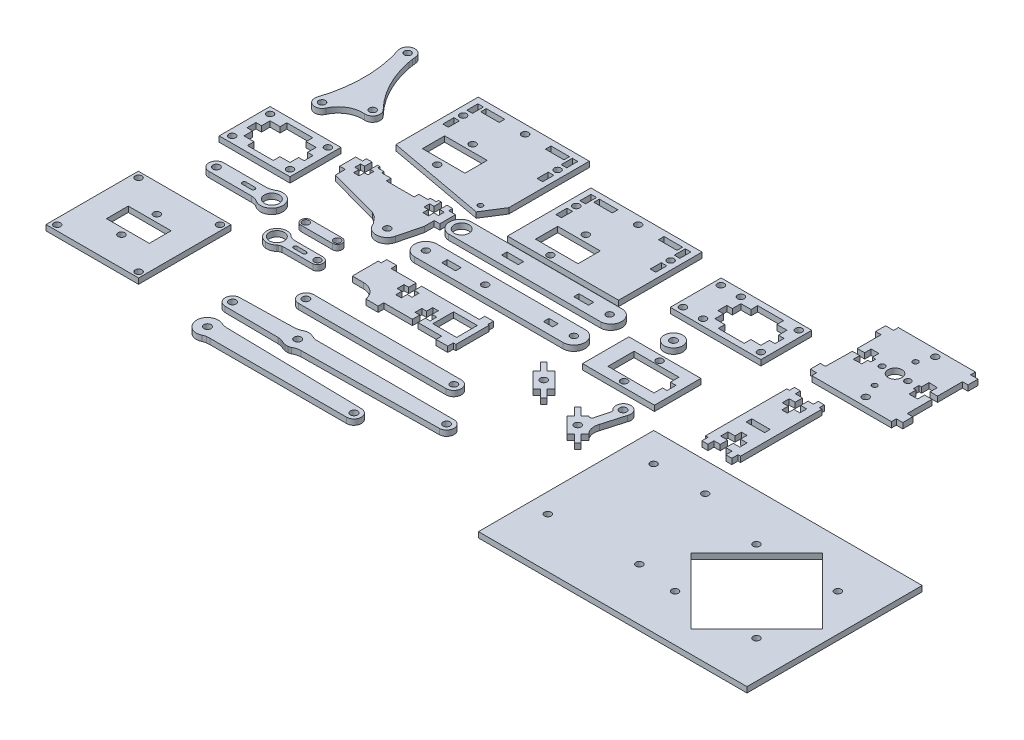
SolidWorks part; units mm, degrees
ref_plane "Front Plane" through (0, 0, 0) normal (0, 0, 1) x (1, 0, 0)
ref_plane "Top Plane" through (0, 0, 0) normal (0, 1, 0) x (1, 0, 0)
ref_plane "Right Plane" through (0, 0, 0) normal (1, 0, 0) x (0, 0, -1)
sketch "Sketch6" plane through (0, 0, -6.8736) normal (0, 1, 0) x (1, 0, 0)
  line L36 (172.3993, 17.524) -> (172.3993, 14.7799)
  line L37 (172.3993, 14.7799) -> (176.2794, 14.7799)
  line L38 (176.2794, 14.7799) -> (176.2794, 10.7799)
  line L39 (176.2794, 10.7799) -> (173.032, 10.7799)
  line L40 (173.032, 10.7799) -> (173.032, 7.063)
  line L41 (173.032, 7.063) -> (176.2794, 7.063)
  line L42 (176.2794, 7.063) -> (176.2794, 3.563)
  line L43 (176.2794, 3.563) -> (179.2794, 3.563)
  line L44 (179.2794, 3.563) -> (179.2794, 7.063)
  line L45 (179.2794, 7.063) -> (182.5439, 7.063)
  line L46 (182.5439, 7.063) -> (182.5439, 10.7799)
  line L47 (182.5439, 10.7799) -> (179.2794, 10.7799)
  line L48 (179.2794, 10.7799) -> (179.2794, 14.7799)
  line L49 (179.2794, 14.7799) -> (182.1277, 14.7799)
  line L50 (182.1277, 14.7799) -> (182.1277, 17.4216)
  line L54 (182.1277, -32.5784) -> (182.1277, -29.2201)
  line L55 (182.1277, -29.2201) -> (178.7635, -29.2201)
  line L56 (178.7635, -29.2201) -> (178.7635, -25.2201)
  line L57 (178.7635, -25.2201) -> (182.3404, -25.2201)
  line L58 (182.3404, -25.2201) -> (182.3404, -21.2526)
  line L59 (182.3404, -21.2526) -> (178.7635, -21.2526)
  line L60 (178.7635, -21.2526) -> (178.7635, -17.7526)
  line L61 (178.7635, -17.7526) -> (175.7635, -17.7526)
  line L62 (175.7635, -17.7526) -> (175.7635, -21.2526)
  line L63 (175.7635, -21.2526) -> (171.9828, -21.2526)
  line L64 (171.9828, -21.2526) -> (171.9828, -25.2201)
  line L65 (171.9828, -25.2201) -> (175.7635, -25.2201)
  line L66 (175.7635, -25.2201) -> (175.7635, -29.2201)
  line L67 (175.7635, -29.2201) -> (172.3993, -29.2201)
  line L68 (172.3993, -29.2201) -> (172.3993, -32.476)
  line L72 (172.2635, -8.7201) -> (182.2635, -8.7201)
  line L73 (182.2635, -8.7201) -> (182.2635, -11.7201)
  line L74 (182.2635, -11.7201) -> (172.2635, -11.7201)
  line L75 (172.2635, -11.7201) -> (172.2635, -8.7201)
  line L132 (186.7635, -29.2201) -> (185.3957, -29.2201)
  line L133 (185.3957, -29.2201) -> (185.3957, -32.5784)
  line L134 (167.7635, -29.2201) -> (169.1313, -29.2201)
  line L135 (169.1313, -29.2201) -> (169.1313, -32.476)
  line L136 (169.1313, 17.524) -> (169.1313, 14.7799)
  line L137 (169.1313, 14.7799) -> (167.7635, 14.7799)
  line L138 (185.3957, 17.4216) -> (185.3957, 14.7799)
  line L139 (185.3957, 14.7799) -> (186.7635, 14.7799)
  line L140 (167.7635, 14.7799) -> (167.7635, -29.2201)
  line L141 (169.1313, -32.476) -> (172.3993, -32.476)
  line L142 (182.1277, 17.4216) -> (185.3957, 17.4216)
  line L143 (186.7635, 14.7799) -> (186.7635, -29.2201)
  line L144 (185.3957, -32.5784) -> (182.1277, -32.5784)
  line L145 (169.1313, 17.524) -> (172.3993, 17.524)
  dimension "D6" = 1.3678
  dimension "D7" = 3.268
extrude "Boss-Extrude1" add sketch "Sketch6" along normal blind 3
sketch "Sketch12" plane through (0, 0, 0) normal (0, 1, 0) x (1, 0, 0)
  line L100 (4.3413, 14.5567) -> (85.6849, 14.5567)
  line L101 (3.678, 2.7449) -> (86.3482, 2.7449)
  line L103 (67.0131, 9.9945) -> (75.0131, 9.9945)
  line L104 (67.0131, 9.9945) -> (67.0131, 7.1945)
  line L105 (67.0131, 7.1945) -> (75.0131, 7.1945)
  line L106 (75.0131, 9.9945) -> (75.0131, 7.1945)
  line L107 (28.0131, 10.0945) -> (37.0131, 10.0945)
  line L108 (28.0131, 10.0945) -> (28.0131, 7.1945)
  line L109 (28.0131, 7.1945) -> (37.0131, 7.1945)
  line L110 (37.0131, 10.0945) -> (37.0131, 7.1945)
  arc A87 (4.3413, 14.5567) -> (3.678, 2.7449) centre (4.3413, 8.6322) ccw
  arc A88 (85.6849, 14.5567) -> (86.3482, 2.7449) centre (85.6849, 8.6322) cw
  circle A100 centre (5.0131, 8.5945) radius 4
  circle A101 centre (85.0131, 8.5945) radius 1.82
  dimension "D29" = 3.64
  dimension "D27" = 8
extrude "Boss-Extrude3" add sketch "Sketch12" along normal blind 3 separate body
sketch "Sketch14" plane through (0, 0, 0) normal (0, 1, 0) x (1, 0, 0)
  line L0 (20.7129, 62.7973) -> (80.7867, 62.7973)
  line L1 (80.7867, 62.7973) -> (80.7867, 17.6847)
  line L2 (80.7867, 17.6847) -> (20.7129, 17.6847)
  line L3 (20.7129, 17.6847) -> (20.7129, 62.7973)
  line L4 (28.2425, 59.822) -> (38.2425, 59.822)
  line L5 (28.2425, 59.822) -> (28.2425, 56.822)
  line L6 (28.2425, 56.822) -> (38.2425, 56.822)
  line L7 (38.2425, 59.822) -> (38.2425, 56.822)
  line L8 (63.2425, 59.822) -> (73.2425, 59.822)
  line L9 (63.2425, 59.822) -> (63.2425, 56.822)
  line L10 (63.2425, 56.822) -> (73.2425, 56.822)
  line L11 (73.2425, 59.822) -> (73.2425, 56.822)
  line L12 (74.7425, 59.822) -> (77.7425, 59.822)
  line L13 (74.7425, 59.822) -> (74.7425, 53.822)
  line L14 (74.7425, 53.822) -> (77.7425, 53.822)
  line L15 (77.7425, 59.822) -> (77.7425, 53.822)
  line L16 (74.7425, 46.822) -> (77.7425, 46.822)
  line L17 (74.7425, 46.822) -> (74.7425, 40.822)
  line L18 (74.7425, 40.822) -> (77.7425, 40.822)
  line L19 (77.7425, 46.822) -> (77.7425, 40.822)
  line L20 (29.7425, 35.822) -> (52.7425, 35.822)
  line L21 (29.7425, 35.822) -> (29.7425, 23.822)
  line L22 (29.7425, 23.822) -> (52.7425, 23.822)
  line L23 (52.7425, 35.822) -> (52.7425, 23.822)
  line L24 (23.7425, 46.822) -> (26.7425, 46.822)
  line L25 (23.7425, 46.822) -> (23.7425, 40.822)
  line L26 (23.7425, 40.822) -> (26.7425, 40.822)
  line L27 (26.7425, 46.822) -> (26.7425, 40.822)
  line L28 (23.7425, 59.822) -> (26.7425, 59.822)
  line L29 (23.7425, 59.822) -> (23.7425, 53.822)
  line L30 (23.7425, 53.822) -> (26.7425, 53.822)
  line L31 (26.7425, 59.822) -> (26.7425, 53.822)
  circle A0 centre (50.7425, 58.322) radius 1.82
  circle A1 centre (41.2425, 39.4969) radius 1.82
  circle A2 centre (41.2425, 20.3569) radius 1.82
  circle A3 centre (76.2425, 50.322) radius 1.82
  circle A4 centre (25.2425, 50.322) radius 1.82
  dimension "D1" = 19.14
  dimension "D2" = 3.64
  dimension "D3" = 3.64
  dimension "D4" = 3.64
  dimension "D5" = 3.64
extrude "Boss-Extrude4" add sketch "Sketch14" along normal blind 3 separate body
sketch "Sketch18" plane through (0, 0, 0) normal (0, 1, 0) x (1, 0, 0)
  line L0 (-52.2788, 74.8705) -> (7.7767, 74.8705)
  line L1 (7.7767, 74.8705) -> (7.7767, 31.3788)
  line L2 (7.7767, 31.3788) -> (0.9291, 20.5522)
  line L3 (0.9291, 20.5522) -> (-52.2788, 30.361)
  line L4 (-52.2788, 30.361) -> (-52.2788, 74.8705)
  line L5 (-44.7078, 71.6303) -> (-34.7078, 71.6303)
  line L6 (-44.7078, 71.6303) -> (-44.7078, 68.6303)
  line L7 (-44.7078, 68.6303) -> (-34.7078, 68.6303)
  line L8 (-34.7078, 71.6303) -> (-34.7078, 68.6303)
  line L9 (-49.2078, 71.6303) -> (-46.2078, 71.6303)
  line L10 (-49.2078, 71.6303) -> (-49.2078, 65.6303)
  line L11 (-49.2078, 65.6303) -> (-46.2078, 65.6303)
  line L12 (-46.2078, 71.6303) -> (-46.2078, 65.6303)
  line L13 (-49.2078, 58.6303) -> (-46.2078, 58.6303)
  line L14 (-49.2078, 58.6303) -> (-49.2078, 52.6303)
  line L15 (-49.2078, 52.6303) -> (-46.2078, 52.6303)
  line L16 (-46.2078, 58.6303) -> (-46.2078, 52.6303)
  line L17 (-43.2078, 47.6303) -> (-20.2078, 47.6303)
  line L18 (-43.2078, 47.6303) -> (-43.2078, 35.6303)
  line L19 (-43.2078, 35.6303) -> (-20.2078, 35.6303)
  line L20 (-20.2078, 47.6303) -> (-20.2078, 35.6303)
  line L21 (-9.7078, 71.6303) -> (0.2922, 71.6303)
  line L22 (-9.7078, 71.6303) -> (-9.7078, 68.6303)
  line L23 (-9.7078, 68.6303) -> (0.2922, 68.6303)
  line L24 (0.2922, 71.6303) -> (0.2922, 68.6303)
  line L25 (1.7922, 71.6303) -> (4.7922, 71.6303)
  line L26 (1.7922, 71.6303) -> (1.7922, 65.6303)
  line L27 (1.7922, 65.6303) -> (4.7922, 65.6303)
  line L28 (4.7922, 71.6303) -> (4.7922, 65.6303)
  line L29 (1.7922, 58.6303) -> (4.7922, 58.6303)
  line L30 (1.7922, 58.6303) -> (1.7922, 52.6303)
  line L31 (1.7922, 52.6303) -> (4.7922, 52.6303)
  line L32 (4.7922, 58.6303) -> (4.7922, 52.6303)
  circle A0 centre (3.3054, 62.1514) radius 1.82
  circle A1 centre (-0.9558, 24.7244) radius 1.2998
  circle A2 centre (-31.7081, 32.1289) radius 1.82
  circle A3 centre (-31.6898, 51.2689) radius 1.82
  circle A4 centre (-47.7078, 62.1303) radius 1.82
  circle A5 centre (-22.2078, 70.1303) radius 1.82
  dimension "D1" = 3.64
  dimension "D2" = 19.14
sketch "Sketch20" plane through (0, 0, 0) normal (0, 1, 0) x (1, 0, 0)
  line L0 (-3.3445, 5.1376) -> (-6.3445, 5.1376)
  line L1 (-6.3445, -0.1855) -> (-9.5309, -12.7114)
  line L2 (-21.2346, -12.8672) -> (-24.3389, -9.2481)
  line L3 (-24.3389, -9.2481) -> (-27.0786, -7.6072)
  line L4 (-27.0786, -7.6072) -> (-54.3445, -0.2275)
  line L5 (-54.3445, -0.2275) -> (-54.3445, 5.0581)
  line L6 (-54.3445, 5.0581) -> (-57.3445, 5.0581)
  line L7 (-57.3445, 5.0581) -> (-57.3445, 13.6523)
  line L8 (-57.3445, 13.6523) -> (-53.6006, 13.6523)
  line L9 (-53.6006, 13.6523) -> (-53.6006, 15.7725)
  line L10 (-53.6006, 15.7725) -> (-50.5945, 15.7725)
  line L11 (-50.5945, 15.7725) -> (-50.5945, 11.7725)
  line L12 (-50.5945, 11.7725) -> (-52.7659, 11.7725)
  line L13 (-52.7659, 11.7725) -> (-52.7659, 8.6302)
  line L14 (-52.7659, 8.6302) -> (-50.5945, 8.6302)
  line L15 (-50.5945, 8.6302) -> (-50.5945, 5.7725)
  line L16 (-50.5945, 5.7725) -> (-47.5945, 5.7725)
  line L17 (-47.5945, 5.7725) -> (-47.5945, 8.6302)
  line L18 (-47.5945, 8.6302) -> (-45.6767, 8.6302)
  line L19 (-45.6767, 8.6302) -> (-45.6767, 11.7725)
  line L20 (-45.6767, 11.7725) -> (-47.5945, 11.7725)
  line L21 (-47.5945, 11.7725) -> (-47.5945, 15.7725)
  line L22 (-47.5945, 15.7725) -> (-46.26, 15.7725)
  line L23 (-46.26, 15.7725) -> (-46.26, 14.5225)
  line L24 (-46.26, 14.5225) -> (-42.8445, 14.5225)
  line L25 (-42.8445, 14.5225) -> (-42.8445, 13.2725)
  line L26 (-42.8445, 13.2725) -> (-37.8445, 13.2725)
  line L27 (-37.8445, 13.2725) -> (-37.8445, 10.7725)
  line L28 (-37.8445, 10.7725) -> (-22.8445, 10.7725)
  line L29 (-22.8445, 10.7725) -> (-22.8445, 13.2725)
  line L30 (-22.8445, 13.2725) -> (-17.8445, 13.2725)
  line L31 (-17.8445, 13.2725) -> (-17.8445, 14.5225)
  line L32 (-17.8445, 14.5225) -> (-14.6403, 14.5225)
  line L33 (-14.6403, 14.5225) -> (-14.6403, 15.7725)
  line L34 (-14.6403, 15.7725) -> (-13.0945, 15.7725)
  line L35 (-13.0945, 15.7725) -> (-13.0945, 11.7725)
  line L36 (-13.0945, 11.7725) -> (-15.4488, 11.7725)
  line L37 (-15.4488, 11.7725) -> (-15.4488, 8.6851)
  line L38 (-15.4488, 8.6851) -> (-13.0945, 8.6851)
  line L39 (-13.0945, 8.6851) -> (-13.0945, 5.7725)
  line L40 (-13.0945, 5.7725) -> (-10.0945, 5.7725)
  line L41 (-10.0945, 5.7725) -> (-10.0945, 8.6674)
  line L42 (-10.0945, 8.6674) -> (-7.5507, 8.6674)
  line L43 (-7.5507, 8.6674) -> (-7.5507, 11.7725)
  line L44 (-7.5507, 11.7725) -> (-10.0945, 11.7725)
  line L45 (-10.0945, 11.7725) -> (-10.0945, 15.7725)
  line L46 (-10.0945, 15.7725) -> (-7.0098, 15.7725)
  line L47 (-7.0098, 15.7725) -> (-7.0098, 13.684)
  line L48 (-7.0098, 13.684) -> (-3.3445, 13.6514)
  line L49 (-3.3445, 13.6514) -> (-3.3445, 5.1376)
  line L50 (-6.3445, 5.1376) -> (-6.3445, -0.1855)
  arc A0 (-9.5309, -12.7114) -> (-21.2346, -12.8672) centre (-15.4037, -11.2174) cw
  circle A1 centre (-15.3445, -11.2275) radius 1.82
  dimension "D1" = 3.64
sketch "Sketch22" plane through (0, 0, 0) normal (0, 1, 0) x (1, 0, 0)
  line L0 (-22.8304, -83.5062) -> (5.98, -82.8529)
  line L1 (18.5125, -82.749) -> (92.2578, -82.749)
  line L2 (92.3104, -90.7487) -> (18.5715, -91.7184)
  line L3 (6.0387, -91.7793) -> (-22.7778, -91.5049)
  arc A0 (5.98, -82.8529) -> (10.0623, -81.6918) centre (5.7889, -74.4239) ccw
  arc A1 (10.0623, -81.6918) -> (10.658, -81.4927) centre (10.8295, -82.9967) cw
  arc A2 (10.658, -81.4927) -> (11.2714, -81.3569) centre (10.3161, -78.495) ccw
  arc A3 (11.2714, -81.3569) -> (11.8955, -81.2861) centre (11.7502, -82.7912) cw
  arc A4 (11.8955, -81.2861) -> (12.5237, -81.2808) centre (12.1844, -78.2942) ccw
  arc A5 (12.5237, -81.2808) -> (13.1489, -81.3413) centre (12.6941, -82.7806) cw
  arc A6 (13.1489, -81.3413) -> (13.7644, -81.4668) centre (14.0525, -78.4818) ccw
  arc A7 (13.7644, -81.4668) -> (14.3634, -81.656) centre (13.6195, -82.9685) cw
  arc A8 (14.3634, -81.656) -> (14.9394, -81.9067) centre (15.8391, -79.0526) ccw
  arc A9 (14.9394, -81.9067) -> (15.6165, -82.2065) centre (13.9387, -85.0813) cw
  arc A10 (15.6165, -82.2065) -> (16.3185, -82.4423) centre (16.5367, -80.6298) ccw
  arc A11 (16.3185, -82.4423) -> (17.0393, -82.6122) centre (15.9213, -85.7415) cw
  arc A12 (17.0393, -82.6122) -> (17.7727, -82.7147) centre (17.6534, -80.8935) ccw
  arc A13 (17.7727, -82.7147) -> (18.5125, -82.749) centre (17.9898, -86.0281) cw
  arc A14 (92.2578, -82.749) -> (92.3104, -90.7487) centre (92.2578, -86.7491) cw
  arc A15 (18.5715, -91.7184) -> (14.4371, -92.8659) centre (18.6822, -100.1392) ccw
  arc A16 (14.4371, -92.8659) -> (13.8407, -93.0629) centre (13.6751, -91.5605) cw
  arc A17 (13.8407, -93.0629) -> (13.2269, -93.1965) centre (14.1702, -96.0538) ccw
  arc A18 (13.2269, -93.1965) -> (12.6025, -93.2652) centre (12.753, -91.7611) cw
  arc A19 (12.6025, -93.2652) -> (11.9743, -93.2682) centre (12.3027, -96.2616) ccw
  arc A20 (11.9743, -93.2682) -> (11.3493, -93.2055) centre (11.8094, -91.7654) cw
  arc A21 (11.3493, -93.2055) -> (10.7342, -93.0779) centre (10.4346, -96.0685) ccw
  arc A22 (10.7342, -93.0779) -> (10.1359, -92.8866) centre (10.8846, -91.5762) cw
  arc A23 (10.1359, -92.8866) -> (9.5608, -92.6338) centre (8.6482, -95.4904) ccw
  arc A24 (9.5608, -92.6338) -> (8.8936, -92.3352) centre (10.5595, -89.5075) cw
  arc A25 (8.8936, -92.3352) -> (8.202, -92.0988) centre (7.9736, -93.8967) ccw
  arc A26 (8.202, -92.0988) -> (7.4916, -91.9264) centre (8.615, -88.8472) cw
  arc A27 (7.4916, -91.9264) -> (6.7685, -91.8196) centre (6.8709, -93.6279) ccw
  arc A28 (6.7685, -91.8196) -> (6.0387, -91.7793) centre (6.5832, -88.5467) cw
  arc A29 (-22.7778, -91.5049) -> (-22.8304, -83.5062) centre (-22.7397, -87.5052) cw
  circle A30 centre (-22.7398, -87.5051) radius 1.925
  circle A31 centre (12.2595, -87.275) radius 1.925
  circle A32 centre (92.2578, -86.749) radius 1.925
  dimension "D1" = 3.85
  dimension "D2" = 3.85
sketch "Sketch23" plane through (0, 0, 0) normal (0, 1, 0) x (1, 0, 0)
  line L0 (62.0938, -102.6123) -> (-12.185, -101.1529)
  line L1 (62.0145, -110.6115) -> (-11.7091, -110.5993)
  arc A0 (-18.7722, -99.8781) -> (-23.9525, -106.2408) centre (-18.181, -105.6496) ccw
  arc A1 (-23.9525, -106.2408) -> (-20.8301, -111.1061) centre (-17.5842, -105.5884) ccw
  arc A2 (-20.8301, -111.1061) -> (-15.5368, -111.3053) centre (-17.9986, -106.2928) ccw
  arc A3 (-15.5368, -111.3053) -> (-13.6142, -110.7239) centre (-12.8064, -116.8649) cw
  arc A4 (-13.6142, -110.7239) -> (-11.7091, -110.5993) centre (-11.7115, -125.1879) cw
  arc A5 (-18.7722, -99.8781) -> (-14.8108, -100.6548) centre (-18.0664, -106.7687) cw
  arc A6 (-14.8108, -100.6548) -> (-13.5188, -101.0143) centre (-13.353, -97.9172) ccw
  arc A7 (-13.5188, -101.0143) -> (-12.185, -101.1529) centre (-14.2348, -114.3916) cw
  arc A8 (62.0938, -102.6123) -> (62.0145, -110.6115) centre (62.0152, -106.6115) cw
  circle A9 centre (62.0152, -106.6115) radius 1.925
  circle A10 centre (-17.9809, -105.8257) radius 1.925
  dimension "D1" = 3.85
  dimension "D2" = 3.85
sketch "Sketch24" plane through (0, 0, 0) normal (0, 1, 0) x (1, 0, 0)
  line L0 (-90.2893, -24.7085) -> (-67.8284, -24.7085)
  line L1 (-90.2954, -32.7085) -> (-67.194, -32.744)
  line L2 (-75.2787, -28.7329) -> (-70.3703, -28.7329) construction
  line L3 (-75.2787, -27.7198) -> (-70.3703, -27.7198)
  line L4 (-75.2787, -29.7461) -> (-70.3703, -29.7461)
  arc A0 (-67.8284, -24.7085) -> (-62.5705, -23.1591) centre (-67.8284, -15.0125) ccw
  arc A1 (-62.5705, -23.1591) -> (-54.9836, -31.523) centre (-60.3229, -28.7434) cw
  arc A2 (-54.9836, -31.523) -> (-63.9473, -33.5823) centre (-60.343, -28.7329) cw
  arc A3 (-67.194, -32.744) -> (-63.9473, -33.5823) centre (-67.2043, -39.4905) cw
  arc A4 (-75.2787, -27.7198) -> (-75.2787, -29.7461) centre (-75.2787, -28.7329) ccw
  arc A5 (-70.3703, -29.7461) -> (-70.3703, -27.7198) centre (-70.3703, -28.7329) ccw
  circle A6 centre (-90.2893, -28.7085) radius 1.925
  circle A7 centre (-60.2893, -28.7085) radius 4
  arc A8 (-90.2954, -32.7085) -> (-90.2893, -24.7085) centre (-90.2893, -28.7085) cw
  point P13 (-72.8245, -28.7329)
  dimension "D1" = 3.85
  dimension "D2" = 8
sketch "Sketch26" plane through (0, 0, 0) normal (0, 1, 0) x (1, 0, 0)
  line L0 (-87.7528, 74.718) -> (-87.4104, 72.6313)
  line L1 (-87.7528, 74.718) -> (-88.0164, 76.816)
  arc A0 (-88.0164, 76.816) -> (-95.8236, 75.1147) centre (-92.0067, 76.3629) ccw
  arc A1 (-95.8236, 75.1147) -> (-95.7872, 31.4073) centre (-162.8228, 53.2052) cw
  arc A2 (-95.7872, 31.4073) -> (-88.3346, 28.5226) centre (-91.9816, 30.1698) ccw
  arc A3 (-88.3346, 28.5226) -> (-75.123, 36.3095) centre (-76.205, 23.044) cw
  arc A4 (-75.123, 36.3095) -> (-71.9331, 43.1193) centre (-74.7969, 40.3087) ccw
  arc A5 (-71.9331, 43.1193) -> (-87.4104, 72.6313) centre (-30.7636, 83.5248) cw
  circle A6 centre (-74.764, 40.2933) radius 1.82
  circle A7 centre (-91.9939, 30.1381) radius 1.82
  circle A8 centre (-91.9939, 76.3923) radius 1.82
  dimension "D1" = 3.64
  dimension "D2" = 3.64
  dimension "D3" = 3.64
sketch "Sketch27" plane through (0, 0, 0) normal (0, 1, 0) x (1, 0, 0)
  line L0 (-91.9831, 11.0737) -> (-77.9831, 11.0737)
  line L1 (-104.1231, 14.1616) -> (-65.8431, 14.1616)
  line L2 (-104.1231, 14.1616) -> (-104.1231, -13.3284)
  line L3 (-104.1231, -13.3284) -> (-65.8431, -13.3284)
  line L4 (-65.8431, 14.1616) -> (-65.8431, -13.3284)
  line L5 (-77.9831, 11.0737) -> (-77.9831, 7.4737)
  line L6 (-77.9831, 7.4737) -> (-72.5331, 7.4737)
  line L7 (-72.5331, 7.4737) -> (-72.5331, 2.8437)
  line L8 (-69.5331, 2.8437) -> (-69.5331, -2.0063)
  line L9 (-69.5331, -2.0063) -> (-72.5331, -2.0063)
  line L10 (-72.5331, -2.0063) -> (-72.5331, -6.6363)
  line L11 (-72.5331, -6.6363) -> (-77.9831, -6.6363)
  line L12 (-77.9831, -6.6363) -> (-77.9831, -10.2363)
  line L13 (-77.9831, -10.2363) -> (-91.9831, -10.2363)
  line L14 (-91.9831, -10.2363) -> (-91.9831, -6.6384)
  line L15 (-91.9831, -6.6384) -> (-97.4331, -6.6384)
  line L16 (-97.4331, -6.6384) -> (-97.4331, -2.0084)
  line L17 (-97.4331, -2.0084) -> (-100.4331, -2.0084)
  line L18 (-100.4331, -2.0084) -> (-100.4331, 2.8416)
  line L19 (-100.4331, 2.8416) -> (-97.4331, 2.8416)
  line L20 (-97.4331, 2.8416) -> (-97.4331, 7.4716)
  line L21 (-97.4331, 7.4716) -> (-91.9831, 7.4716)
  line L22 (-91.9831, 7.4716) -> (-91.9831, 11.0737)
  line L23 (-72.5331, 2.8437) -> (-69.5331, 2.8437)
  circle A0 centre (-100.6231, 10.6616) radius 1.82
  circle A1 centre (-100.6231, -9.8284) radius 1.82
  circle A2 centre (-69.3431, -9.8263) radius 1.82
  circle A3 centre (-69.3431, 10.6616) radius 1.82
  dimension "D1" = 3.64
  dimension "D2" = 14
  dimension "D3" = 3.6
  dimension "D4" = 3.6
  dimension "D5" = 4.85
  dimension "D6" = 4.63
  dimension "D7" = 3.19
  dimension "D8" = 3.19
  dimension "D9" = 3.19
  dimension "D10" = 5.45
  dimension "D11" = 3
  dimension "D12" = 3.19
  dimension "D13" = 3.19
  dimension "D14" = 3.19
  dimension "D15" = 3.5
  dimension "D16" = 3.5
  dimension "D17" = 3.5
sketch "Sketch28" plane through (0, 0, 0) normal (0, 1, 0) x (1, 0, 0)
  line L0 (108.8597, -2.0432) -> (133.1497, -2.0432)
  line L1 (100.7124, 3.3321) -> (139.6281, 3.3321)
  line L2 (100.7124, 3.3321) -> (100.7124, -21.7433)
  line L3 (100.7124, -21.7433) -> (139.6281, -21.7433)
  line L4 (139.6281, 3.3321) -> (139.6281, -21.7433)
  line L5 (133.1497, -2.0432) -> (133.1497, -6.6732)
  line L6 (133.1497, -6.6732) -> (136.1497, -6.6732)
  line L7 (136.1497, -6.6732) -> (136.1497, -11.5232)
  line L8 (136.1497, -11.5232) -> (133.7949, -11.5232)
  line L9 (133.7949, -11.5232) -> (133.7949, -16.1532)
  line L10 (133.7949, -16.1532) -> (108.8597, -16.1532)
  line L11 (108.8597, -16.1532) -> (108.8597, -2.0432)
  circle A0 centre (120.2396, 0.384) radius 1.82
  circle A1 centre (120.2396, -18.756) radius 1.82
  dimension "D1" = 3.64
  dimension "D2" = 3.64
  dimension "D3" = 3
  dimension "D4" = 24.29
  dimension "D5" = 4.85
  dimension "D6" = 4.63
  dimension "D7" = 19.14
sketch "Sketch29" plane through (0, 0, 0) normal (0, 1, 0) x (1, 0, 0)
  line L0 (120.9256, 52.7526) -> (134.9256, 52.7526)
  line L1 (98.079, 55.8405) -> (147.0656, 55.8405)
  line L2 (98.079, 55.8405) -> (98.079, 28.3505)
  line L3 (98.079, 28.3505) -> (147.0656, 28.3505)
  line L4 (147.0656, 55.8405) -> (147.0656, 28.3505)
  line L5 (134.9256, 52.7526) -> (134.9256, 49.1526)
  line L6 (134.9256, 49.1526) -> (140.3756, 49.1526)
  line L7 (140.3756, 49.1526) -> (140.3756, 44.5226)
  line L8 (143.3756, 44.5226) -> (143.3756, 39.6726)
  line L9 (143.3756, 39.6726) -> (140.3756, 39.6726)
  line L10 (140.3756, 39.6726) -> (140.3756, 35.0426)
  line L11 (140.3756, 35.0426) -> (134.9256, 35.0426)
  line L12 (134.9256, 35.0426) -> (134.9256, 31.4426)
  line L13 (134.9256, 31.4426) -> (120.9256, 31.4426)
  line L14 (120.9256, 31.4426) -> (120.9256, 35.0405)
  line L15 (120.9256, 35.0405) -> (115.4756, 35.0405)
  line L16 (115.4756, 35.0405) -> (115.4756, 39.6705)
  line L17 (115.4756, 39.6705) -> (112.4756, 39.6705)
  line L18 (112.4756, 39.6705) -> (112.4756, 44.5205)
  line L19 (112.4756, 44.5205) -> (115.4756, 44.5205)
  line L20 (115.4756, 44.5205) -> (115.4756, 49.1505)
  line L21 (115.4756, 49.1505) -> (120.9256, 49.1505)
  line L22 (120.9256, 49.1505) -> (120.9256, 52.7526)
  line L23 (140.3756, 44.5226) -> (143.3756, 44.5226)
  circle A0 centre (112.2856, 52.3405) radius 1.82
  circle A1 centre (112.2856, 31.8505) radius 1.82
  circle A2 centre (143.5656, 31.8526) radius 1.82
  circle A3 centre (143.5656, 52.3405) radius 1.82
  circle A4 centre (101.4197, 52.3405) radius 1.82
  circle A5 centre (101.4197, 31.8505) radius 1.82
  dimension "D1" = 3.64
  dimension "D2" = 14
  dimension "D3" = 3.6
  dimension "D4" = 3.6
  dimension "D5" = 4.85
  dimension "D6" = 4.63
  dimension "D7" = 3.19
  dimension "D8" = 3.19
  dimension "D9" = 3.19
  dimension "D10" = 5.45
  dimension "D11" = 3
  dimension "D12" = 3.19
  dimension "D13" = 3.1879
  dimension "D14" = 3.19
  dimension "D15" = 3.5
  dimension "D16" = 3.5
  dimension "D17" = 20.49
sketch "Sketch30" plane through (0, 0, 0) normal (0, 1, 0) x (1, 0, 0)
  line L0 (17.989, -28.9872) -> (4.4448, -28.9872)
  line L1 (11.9231, -50.0571) -> (18.5165, -50.0571)
  line L2 (18.5165, -50.0571) -> (18.5165, -46.9872)
  line L3 (18.5165, -46.9872) -> (33.989, -46.9872)
  line L4 (33.989, -46.9872) -> (33.989, -42.9872)
  line L5 (33.989, -42.9872) -> (31.4392, -42.9872)
  line L6 (31.4392, -42.9872) -> (31.4392, -39.3422)
  line L7 (31.4392, -39.3422) -> (33.989, -39.3422)
  line L8 (33.989, -39.3422) -> (33.989, -35.9872)
  line L9 (33.989, -35.9872) -> (36.989, -35.9872)
  line L10 (36.989, -35.9872) -> (36.989, -39.3774)
  line L11 (36.989, -39.3774) -> (39.5388, -39.3774)
  line L12 (39.5388, -39.3774) -> (39.5388, -42.9872)
  line L13 (39.5388, -42.9872) -> (36.989, -42.9872)
  line L14 (36.989, -42.9872) -> (36.989, -46.9872)
  line L15 (36.989, -46.9872) -> (49.8067, -46.9872)
  line L16 (49.8067, -46.9872) -> (49.8067, -49.9872)
  line L17 (52.1127, -25.9872) -> (52.1127, -28.9872)
  line L18 (52.1127, -28.9872) -> (20.989, -28.9872)
  line L19 (20.989, -28.9872) -> (20.989, -32.9872)
  line L20 (20.989, -32.9872) -> (23.539, -32.9872)
  line L21 (23.539, -32.9872) -> (23.539, -36.7505)
  line L22 (23.539, -36.7505) -> (20.989, -36.7505)
  line L23 (20.989, -36.7505) -> (20.989, -39.9872)
  line L24 (20.989, -39.9872) -> (17.989, -39.9872)
  line L25 (17.989, -39.9872) -> (17.989, -36.6921)
  line L26 (17.989, -36.6921) -> (15.439, -36.6921)
  line L27 (15.439, -36.6921) -> (15.439, -32.9872)
  line L28 (15.439, -32.9872) -> (17.989, -32.9872)
  line L29 (17.989, -32.9872) -> (17.989, -28.9872)
  line L30 (4.4448, -28.9872) -> (4.4448, -25.9872)
  line L31 (41.6011, -32.3441) -> (54.4301, -32.3441)
  line L32 (41.6011, -32.3441) -> (41.6011, -43.5339)
  line L33 (41.6011, -43.5339) -> (54.4301, -43.5339)
  line L34 (54.4301, -32.3441) -> (54.4301, -43.5339)
  line L35 (-2.511, -42.9872) -> (3.489, -42.9872)
  line L36 (-0.8977, -25.9872) -> (-0.8977, -28.9872)
  line L37 (-0.8977, -28.9872) -> (-2.511, -28.9872)
  line L38 (56.0898, -49.9872) -> (56.0898, -46.9872)
  line L39 (56.0898, -46.9872) -> (57.489, -46.9872)
  line L40 (56.7962, -25.9872) -> (56.7962, -28.9872)
  line L41 (56.7962, -28.9872) -> (57.489, -28.9872)
  line L42 (57.489, -28.9872) -> (57.489, -46.9872)
  line L43 (56.0898, -49.9872) -> (49.8067, -49.9872)
  line L44 (56.7962, -25.9872) -> (52.1127, -25.9872)
  line L45 (-0.8977, -25.9872) -> (4.4448, -25.9872)
  line L46 (-2.511, -42.9872) -> (-2.511, -28.9872)
  arc A0 (3.489, -42.9872) -> (11.9231, -50.0571) centre (3.489, -51.5529) cw
  dimension "D1" = 3.645
  dimension "D2" = 2.5498
  dimension "D3" = 2.55
  dimension "D4" = 2.55
  dimension "D5" = 2.55
  dimension "D6" = 2.55
sketch "Sketch31" plane through (0, 0, 0) normal (0, 1, 0) x (1, 0, 0)
  line L0 (-40.1799, -27.8411) -> (-23.1799, -27.8411)
  line L1 (-23.1799, -33.0411) -> (-40.1799, -33.0411)
  arc A0 (-23.1799, -27.8411) -> (-23.1799, -33.0411) centre (-23.1799, -30.4411) cw
  arc A1 (-40.1799, -33.0411) -> (-40.1799, -27.8411) centre (-40.1799, -30.4411) cw
  circle A2 centre (-40.1799, -30.4411) radius 1.82
  circle A3 centre (-23.1799, -30.4411) radius 1.82
  dimension "D1" = 3.64
  dimension "D2" = 3.64
  dimension "D3" = 2.6
  dimension "D4" = 2.6
  dimension "D5" = 2.6
sketch "Sketch32" plane through (0, 0, 0) normal (0, 1, 0) x (1, 0, 0)
  line L0 (-19.3691, -41.9276) -> (-34.5684, -41.9276)
  line L1 (-18.8998, -47.8907) -> (-35.1542, -47.962)
  line L2 (-35.1542, -47.962) -> (-35.7319, -48.0649)
  line L3 (-31.4441, -44.9276) -> (-26.3849, -44.9276) construction
  line L4 (-31.4441, -43.9544) -> (-26.3849, -43.9544)
  line L5 (-31.4441, -45.9008) -> (-26.3849, -45.9008)
  arc A0 (-34.5684, -41.9276) -> (-38.333, -40.3416) centre (-34.5684, -36.6667) cw
  arc A1 (-38.333, -40.3416) -> (-42.1025, -50.3785) centre (-41.3099, -44.9499) ccw
  arc A2 (-42.1025, -50.3785) -> (-37.3382, -48.7649) centre (-41.3026, -44.9) ccw
  arc A3 (-37.3382, -48.7649) -> (-36.8315, -48.4691) centre (-36.5499, -49.5334) cw
  arc A4 (-36.8315, -48.4691) -> (-35.7319, -48.0649) centre (-38.4338, -42.4122) ccw
  arc A5 (-19.3691, -41.9276) -> (-18.8998, -47.8907) centre (-19.3691, -44.9276) cw
  arc A6 (-31.4441, -43.9544) -> (-31.4441, -45.9008) centre (-31.4441, -44.9276) ccw
  arc A7 (-26.3849, -45.9008) -> (-26.3849, -43.9544) centre (-26.3849, -44.9276) ccw
  circle A8 centre (-41.3691, -44.9276) radius 4
  circle A9 centre (-19.3691, -44.9276) radius 1.82
  point P17 (-28.9145, -44.9276)
  dimension "D1" = 3.64
sketch "Sketch33" plane through (0, 0, 0) normal (0, 1, 0) x (1, 0, 0)
  line L0 (-4.2145, -66.2122) -> (75.574, -66.2122) construction
  line L1 (-4.2145, -62.1261) -> (75.574, -62.1261)
  line L2 (-4.2145, -70.2983) -> (75.574, -70.2983)
  arc A0 (-4.2145, -62.1261) -> (-4.2145, -70.2983) centre (-4.2145, -66.2122) ccw
  arc A1 (75.574, -70.2983) -> (75.574, -62.1261) centre (75.574, -66.2122) ccw
  circle A2 centre (-4.3278, -66.2456) radius 1.87
  circle A3 centre (75.6722, -66.2456) radius 1.87
  point P2 (35.6798, -66.2122)
  dimension "D1" = 3.74
  dimension "D2" = 3.74
sketch "Sketch34" plane through (0, 0, 0) normal (0, 1, 0) x (1, 0, 0)
  line L0 (85.46, -5.1233) -> (5.46, -5.1233)
  line L1 (5.3693, -17.1401) -> (85.46, -17.1233)
  line L2 (85.46, -17.1401) -> (85.46, -17.1233)
  line L3 (15.46, -9.6233) -> (22.96, -9.6233)
  line L4 (15.46, -9.6233) -> (15.46, -12.6233)
  line L5 (15.46, -12.6233) -> (22.96, -12.6233)
  line L6 (22.96, -9.6233) -> (22.96, -12.6233)
  line L7 (70.46, -9.6233) -> (75.46, -9.6233)
  line L8 (70.46, -9.6233) -> (70.46, -12.6233)
  line L9 (70.46, -12.6233) -> (75.46, -12.6233)
  line L10 (75.46, -9.6233) -> (75.46, -12.6233)
  arc A0 (5.46, -5.1233) -> (5.3693, -17.1401) centre (5.4147, -11.1317) ccw
  arc A1 (85.46, -5.1233) -> (85.46, -17.1401) centre (85.46, -11.1317) cw
  circle A2 centre (85.46, -11.1233) radius 1.82
  circle A3 centre (37.46, -11.1233) radius 1.82
  circle A4 centre (5.46, -11.1233) radius 1.82
  dimension "D1" = 3.64
  dimension "D2" = 3.64
  dimension "D3" = 3.64
sketch "Sketch35" plane through (0, 0, 0) normal (0, 1, 0) x (1, 0, 0)
  circle A0 centre (114.4508, 13.6733) radius 1.925
  circle A1 centre (114.4508, 13.6733) radius 5
  dimension "D1" = 3.85
sketch "Sketch36" plane through (0, 0, 0) normal (0, 1, 0) x (1, 0, 0)
  line L0 (96.6735, -32.7093) -> (105.1588, -41.1946)
  line L1 (105.1588, -41.1946) -> (103.0375, -43.3159)
  line L2 (103.0375, -43.3159) -> (107.2801, -47.5586)
  line L3 (107.2801, -47.5586) -> (105.583, -49.2556)
  line L4 (105.583, -49.2556) -> (101.3404, -45.013)
  line L5 (101.3404, -45.013) -> (99.2191, -47.1343)
  line L6 (99.2191, -47.1343) -> (90.7338, -38.6491)
  line L7 (90.7338, -38.6491) -> (92.8551, -36.5277)
  line L8 (92.8551, -36.5277) -> (88.6125, -32.2851)
  line L9 (88.6125, -32.2851) -> (90.3095, -30.588)
  line L10 (90.3095, -30.588) -> (94.5522, -34.8307)
  line L11 (94.5522, -34.8307) -> (96.6735, -32.7093)
  circle A0 centre (97.9463, -39.9218) radius 1.82
  dimension "D1" = 3.64
sketch "Sketch37" plane through (0, 0, 0) normal (0, 1, 0) x (1, 0, 0)
  line L0 (135.4169, -53.0651) -> (133.2956, -55.1864)
  line L1 (133.2956, -55.1864) -> (137.5382, -59.4291)
  line L2 (137.5382, -59.4291) -> (135.8412, -61.1261)
  line L3 (135.8412, -61.1261) -> (131.5985, -56.8835)
  line L4 (131.5985, -56.8835) -> (129.4772, -59.0048)
  line L5 (129.4772, -59.0048) -> (120.9919, -50.5195)
  line L6 (120.9919, -50.5195) -> (123.1132, -48.3982)
  line L7 (123.1132, -48.3982) -> (118.8706, -44.1556)
  line L8 (118.8706, -44.1556) -> (120.5677, -42.4585)
  line L9 (120.5677, -42.4585) -> (124.8103, -46.7012)
  line L10 (124.8103, -46.7012) -> (126.9316, -44.5798)
  line L11 (129.1898, -43.6445) -> (131.0313, -36.7977)
  line L12 (133.7199, -45.6405) -> (137.1051, -33.9217)
  line L13 (131.0313, -36.7977) -> (131.0313, -35.5609)
  arc A0 (126.9316, -44.5798) -> (129.1898, -43.6445) centre (127.867, -43.6445) ccw
  arc A1 (135.4169, -53.0651) -> (133.7199, -45.6405) centre (140.4805, -48.0015) cw
  circle A2 centre (133.3808, -32.4738) radius 1.925
  arc A3 (137.1051, -33.9217) -> (131.0313, -35.5609) centre (133.4056, -32.2861) ccw
  circle A4 centre (128.2044, -51.7923) radius 1.8201
  dimension "D1" = 3.6402
  dimension "D2" = 3.85
sketch "Sketch38" plane through (0, 0, 0) normal (0, 1, 0) x (1, 0, 0)
  line L0 (214.8986, 72.4925) -> (211.8986, 72.4925)
  line L1 (211.8986, 72.4925) -> (211.8986, 59.0158)
  line L2 (211.8986, 59.0158) -> (207.8986, 59.0158)
  line L3 (207.8986, 59.0158) -> (207.8986, 62.9131)
  line L4 (207.8986, 62.9131) -> (203.2662, 63.0537)
  line L5 (203.2662, 63.0537) -> (203.2662, 59.0158)
  line L6 (203.2662, 59.0158) -> (201.8986, 59.0158)
  line L7 (201.8986, 59.0158) -> (201.8986, 56.0158)
  line L8 (201.8986, 56.0158) -> (203.2651, 56.0158)
  line L9 (203.2651, 56.0158) -> (203.2651, 52.2449)
  line L10 (203.2651, 52.2449) -> (207.8986, 52.2911)
  line L11 (207.8986, 52.2911) -> (207.8986, 56.0158)
  line L12 (207.8986, 56.0158) -> (211.8986, 56.0158)
  line L13 (211.8986, 56.0158) -> (211.8986, 42.6429)
  line L14 (211.8986, 42.6429) -> (214.8986, 42.6429)
  line L15 (164.8986, 42.6429) -> (167.6736, 42.6429)
  line L16 (167.8986, 56.962) -> (171.8986, 56.962)
  line L17 (171.8986, 56.962) -> (171.8986, 53.4656)
  line L18 (171.8986, 53.4656) -> (176.3141, 53.6437)
  line L19 (176.3141, 53.6437) -> (176.3141, 56.962)
  line L20 (176.3141, 56.962) -> (177.8986, 56.962)
  line L21 (177.8986, 56.962) -> (177.8986, 59.6133)
  line L22 (177.8986, 59.6133) -> (176.1034, 59.6133)
  line L23 (176.1034, 59.6133) -> (176.1034, 63.1125)
  line L24 (176.1034, 63.1125) -> (171.8986, 63.1125)
  line L25 (171.8986, 63.1125) -> (171.8986, 59.6133)
  line L26 (171.8986, 59.6133) -> (167.8986, 59.6133)
  line L27 (167.8986, 59.6133) -> (167.8986, 72.4925)
  line L28 (167.8986, 72.4925) -> (164.8986, 72.4925)
  line L29 (167.6736, 42.6429) -> (167.8986, 56.962)
  line L30 (214.8986, 37.2429) -> (211.4066, 37.2429)
  line L31 (211.4066, 37.2429) -> (211.4066, 34.6032)
  line L32 (164.8986, 37.2429) -> (168.3401, 37.2429)
  line L33 (168.3401, 37.2429) -> (168.3401, 34.6032)
  line L34 (214.8986, 37.2429) -> (214.8986, 42.6429)
  line L35 (211.4066, 34.6032) -> (168.3401, 34.6032)
  line L36 (164.8986, 37.2429) -> (164.8986, 42.6429)
  line L37 (210.8826, 80.5322) -> (210.8826, 77.8925)
  line L38 (210.8826, 77.8925) -> (214.8986, 77.8925)
  line L39 (164.8986, 77.8925) -> (169.2475, 77.8925)
  line L40 (169.2475, 77.8925) -> (169.2475, 80.5322)
  line L41 (169.2475, 80.5322) -> (210.8826, 80.5322)
  line L42 (164.8986, 77.8925) -> (164.8986, 72.4925)
  line L43 (214.8986, 72.4925) -> (214.8986, 77.8925)
  circle A0 centre (189.8986, 58.0322) radius 3.75
  circle A1 centre (182.8986, 58.0322) radius 1.5333
  circle A2 centre (189.889, 69.1146) radius 1.4239
  circle A3 centre (196.8493, 58.0203) radius 1.6482
  circle A4 centre (192.8986, 76.7822) radius 1.82
  circle A5 centre (189.8986, 47.0381) radius 1.3524
  circle A6 centre (192.885, 39.1928) radius 1.82
  dimension "D6" = 3.64
  dimension "D7" = 3.64
  dimension "D1" = 5.4
  dimension "D2" = 5.4
  dimension "D3" = 5.4
  dimension "D4" = 5.4
  dimension "D5" = 2.6397
extrude "Boss-Extrude5" add sketch "Sketch18" along normal blind 3 separate body
extrude "Boss-Extrude6" add sketch "Sketch38" along normal blind 3 separate body
extrude "Boss-Extrude7" add sketch "Sketch37" along normal blind 3 separate body
extrude "Boss-Extrude8" add sketch "Sketch36" along normal blind 3 separate body
extrude "Boss-Extrude9" add sketch "Sketch35" along normal blind 3 separate body
extrude "Boss-Extrude10" add sketch "Sketch34" along normal blind 3 separate body
extrude "Boss-Extrude11" add sketch "Sketch33" along normal blind 3 separate body
extrude "Boss-Extrude12" add sketch "Sketch32" along normal blind 3 separate body
extrude "Boss-Extrude13" add sketch "Sketch31" along normal blind 3 separate body
extrude "Boss-Extrude14" add sketch "Sketch30" along normal blind 3 separate body
extrude "Boss-Extrude15" add sketch "Sketch29" along normal blind 3 separate body
extrude "Boss-Extrude16" add sketch "Sketch28" along normal blind 3 separate body
extrude "Boss-Extrude17" add sketch "Sketch27" along normal blind 3 separate body
extrude "Boss-Extrude18" add sketch "Sketch26" along normal blind 3 separate body
extrude "Boss-Extrude19" add sketch "Sketch24" along normal blind 3 separate body
extrude "Boss-Extrude20" add sketch "Sketch23" along normal blind 3 separate body
extrude "Boss-Extrude21" add sketch "Sketch22" along normal blind 3 separate body
extrude "Boss-Extrude22" add sketch "Sketch20" along normal blind 3 separate body
sketch "Sketch41" plane through (0, 0, 0) normal (0, 1, 0) x (1, 0, 0)
  line L0 (218.7805, -81.1114) -> (254.3702, -116.7011)
  line L1 (151.2617, -33.8089) -> (296.4281, -33.8089)
  line L2 (151.2617, -33.8089) -> (151.2617, -128.5401)
  line L3 (151.2617, -128.5401) -> (296.4281, -128.5401)
  line L4 (296.4281, -33.8089) -> (296.4281, -128.5401)
  line L5 (254.3702, -116.7011) -> (289.8339, -81.2374)
  line L6 (289.8339, -81.2374) -> (254.2442, -45.6477)
  line L7 (254.2442, -45.6477) -> (218.7805, -81.1114)
  circle A0 centre (232.313, -59.3089) radius 1.82
  circle A1 centre (194.813, -49.5089) radius 1.82
  circle A2 centre (166.913, -49.5089) radius 1.82
  circle A3 centre (161.813, -101.6089) radius 1.82
  circle A4 centre (210.013, -100.3089) radius 1.82
  circle A5 centre (232.313, -103.3089) radius 1.82
  circle A6 centre (276.313, -103.3089) radius 1.82
  circle A7 centre (276.313, -59.3089) radius 1.82
  dimension "D1" = 3.64
extrude "Boss-Extrude23" add sketch "Sketch41" along normal blind 3 separate body
sketch "Sketch42" plane through (0, 0, 0) normal (0, 1, 0) x (1, 0, 0)
  line L0 (-109.4446, -51.7385) -> (-59.3919, -51.7385)
  line L1 (-109.4446, -51.7385) -> (-109.4446, -101.6556)
  line L2 (-109.4446, -101.6556) -> (-59.3919, -101.6556)
  line L3 (-59.3919, -51.7385) -> (-59.3919, -101.6556)
  line L4 (-95.8417, -82.5662) -> (-72.6942, -82.5662)
  line L5 (-95.8417, -82.5662) -> (-95.8417, -70.7669)
  line L6 (-95.8417, -70.7669) -> (-72.6942, -70.7669)
  line L7 (-72.6942, -82.5662) -> (-72.6942, -70.7669)
  circle A0 centre (-106.3103, -54.7462) radius 1.82
  circle A1 centre (-84.3064, -66.8836) radius 1.82
  circle A2 centre (-62.3037, -54.735) radius 1.82
  circle A3 centre (-84.3093, -86.0236) radius 1.82
  circle A4 centre (-62.3053, -98.732) radius 1.82
  circle A5 centre (-106.3086, -98.7412) radius 1.82
  dimension "D1" = 19.14
  dimension "D2" = 3.64
extrude "Boss-Extrude24" add sketch "Sketch42" along normal blind 3 separate body
